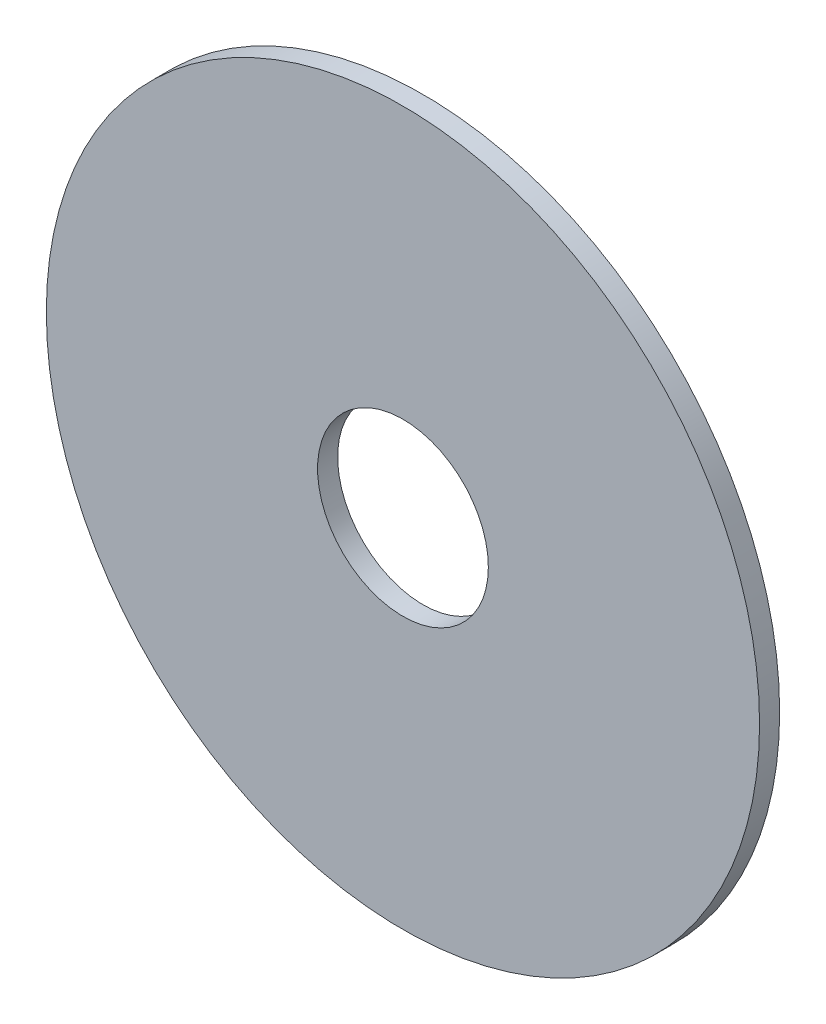
SolidWorks part; units mm, degrees
ref_plane "Alzado" through (0, 0, 0) normal (0, 0, 1) x (1, 0, 0)
ref_plane "Planta" through (0, 0, 0) normal (0, 1, 0) x (1, 0, 0)
ref_plane "Vista lateral" through (0, 0, 0) normal (1, 0, 0) x (0, 0, -1)
sketch "Croquis2" plane through (0, 0, 0) normal (0, 0, 1) x (1, 0, 0)
sketch_block_instance "v-1"
sketch_block "Bloque1"
sketch "Croquis4" plane through (0, 0, 0) normal (0, 0, 1) x (1, 0, 0)
  line L0 (0, 57.5) -> (0, 177.5) construction
  line L1 (28.75, 49.7965) -> (88.75, 153.7195) construction
  line L2 (49.7965, 28.75) -> (153.7195, 88.75) construction
  line L3 (57.5, 0) -> (177.5, 0) construction
  line L4 (49.7965, -28.75) -> (153.7195, -88.75) construction
  line L5 (28.75, -49.7965) -> (88.75, -153.7195) construction
  line L6 (0, -57.5) -> (0, -177.5) construction
  line L7 (-28.75, -49.7965) -> (-88.75, -153.7195) construction
  line L8 (-49.7965, -28.75) -> (-153.7195, -88.75) construction
  line L9 (-57.5, 0) -> (-177.5, 0) construction
  line L10 (-49.7965, 28.75) -> (-153.7195, 88.75) construction
  line L11 (-28.75, 49.7965) -> (-88.75, 153.7195) construction
  circle A0 centre (0, 0) radius 177.5
  circle A1 centre (0, 0) radius 216.259
  circle A2 centre (0, 0) radius 57.5
  circle A3 centre (0, 0) radius 42.5
  arc A4 (57.5, 0) -> (177.5, 0) centre (117.5, -153.7043) cw
  arc A5 (49.7965, -28.75) -> (153.7195, -88.75) centre (24.9059, -191.8618) cw
  arc A6 (28.75, -49.7965) -> (88.75, -153.7195) centre (-74.3618, -178.6101) cw
  arc A7 (0, -57.5) -> (0, -177.5) centre (-153.7043, -117.5) cw
  arc A8 (-28.75, -49.7965) -> (-88.75, -153.7195) centre (-191.8618, -24.9059) cw
  arc A9 (-49.7965, -28.75) -> (-153.7195, -88.75) centre (-178.6101, 74.3618) cw
  arc A10 (-57.5, 0) -> (-177.5, 0) centre (-117.5, 153.7043) cw
  arc A11 (-49.7965, 28.75) -> (-153.7195, 88.75) centre (-24.9059, 191.8618) cw
  arc A12 (-28.75, 49.7965) -> (-88.75, 153.7195) centre (74.3618, 178.6101) cw
  arc A13 (0, 57.5) -> (0, 177.5) centre (153.7043, 117.5) cw
  arc A14 (28.75, 49.7965) -> (88.75, 153.7195) centre (191.8618, 24.9059) cw
  arc A15 (49.7965, 28.75) -> (153.7195, 88.75) centre (178.6101, -74.3618) cw
  point P32 (0, 0)
  point P67 (0, 0)
  dimension "D1" = 355
  dimension "D2" = 432.518
  dimension "D3" = 115
  dimension "D4" = 85
  dimension "D6" = 12
  dimension "D7" = 122.8156
  dimension "D5" = 12
sketch "Croquis6" plane through (0, 0, 0) normal (0, 0, 1) x (1, 0, 0)
  circle A0 centre (0, 0) radius 177.5
  circle A1 centre (0, 0) radius 42.5
extrude "Saliente-Extruir1" add sketch "Croquis6" along normal blind 10
